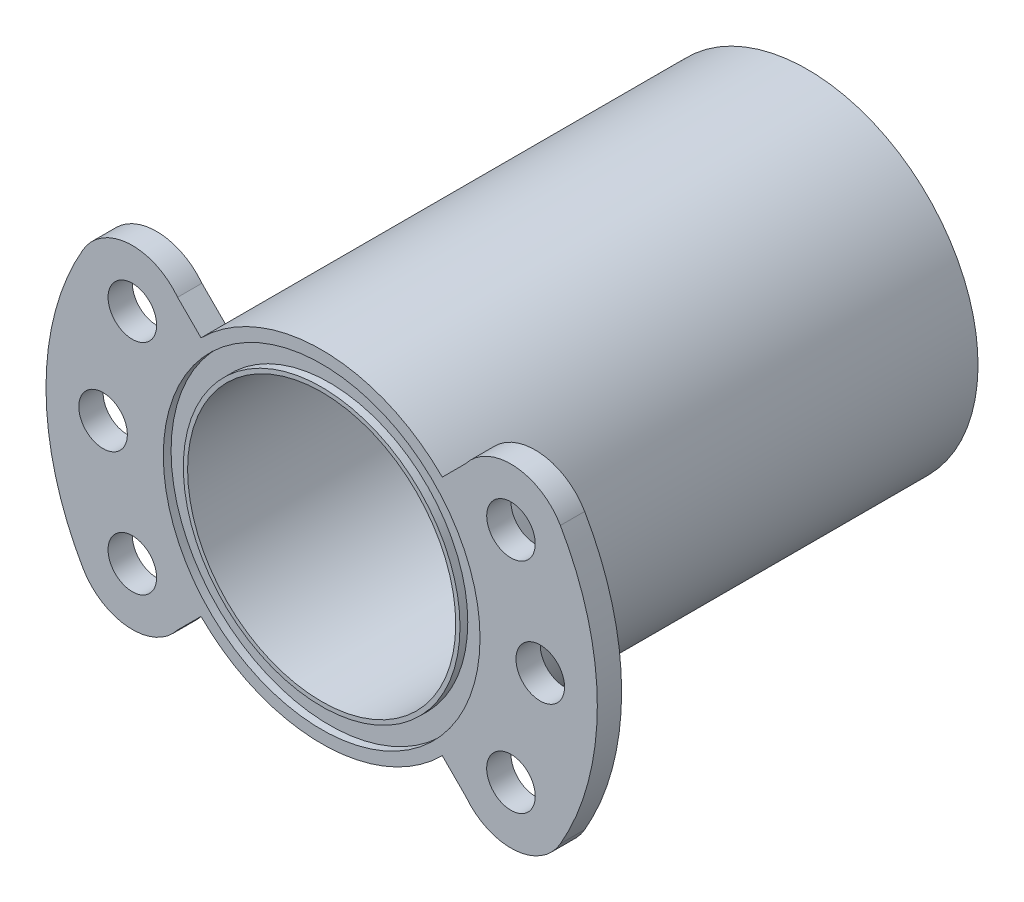
SolidWorks part; units mm, degrees
material "6061-T6 (SS)"
ref_plane "Front Plane" through (0, 0, 0) normal (0, 0, 1) x (1, 0, 0)
ref_plane "Top Plane" through (0, 0, 0) normal (0, 1, 0) x (1, 0, 0)
ref_plane "Right Plane" through (0, 0, 0) normal (1, 0, 0) x (0, 0, -1)
sketch "Sketch1" plane through (0, 0, 0) normal (0, 0, 1) x (1, 0, 0)
  circle A0 centre (0, 0) radius 17.526
  circle A1 centre (0, 0) radius 21.082
  dimension "D1" = 3.556
  dimension "D2" = 35.052
  dimension "D3" = 42.164
extrude "Boss-Extrude1" add sketch "Sketch1" along normal blind 254
sketch "Sketch2" plane through (0, 0, 0) normal (0, 0, -1) x (-1, 0, 0)
  circle A0 centre (0, 0) radius 21.082
extrude "Boss-Extrude2" add sketch "Sketch2" along normal blind 6.35
sketch "Sketch3" plane through (0, 0, 254) normal (0, 0, 1) x (1, 0, 0)
  circle A0 centre (0, 0) radius 25.8684
extrude "Cut-Extrude1" cut sketch "Sketch3" against normal blind 127
sketch "Sketch4" plane through (0, 0, 127) normal (0, 0, 1) x (1, 0, 0)
  circle A0 centre (0, 0) radius 19.0911
  circle A1 centre (0, 0) radius 34.925
  dimension "D1" = 69.85
extrude "Boss-Extrude3" add sketch "Sketch4" against normal blind 3.175
sketch "Sketch5" plane through (0, 0, 127) normal (0, 0, 1) x (1, 0, 0)
  line L0 (0, 0) -> (0, 17.526)
  line L1 (0, 17.526) -> (0, 34.925)
  circle A0 centre (0, 0) radius 17.526 construction
  circle A3 centre (0, 0) radius 34.925 construction
  circle A4 centre (0, 28.575) radius 3.175
  circle A5 centre (0, 28.575) radius 6.35
  dimension "D1" = 6.35
  dimension "D2" = 12.7
  dimension "D3" = 28.575
extrude "Cut-Extrude2" cut sketch "Sketch5" against normal through all contours L1 A4 | L1 A4
pattern_circular "CirPattern1" count 12 every 30 about axis through (0, 0, 0) along (0, 0, 1) of "Cut-Extrude2"
sketch "Sketch6" plane through (0, 0, -6.35) normal (0, 0, -1) x (-1, 0, 0)
  circle A0 centre (0, 0) radius 21.082
extrude "Cut-Extrude3" cut sketch "Sketch6" against normal blind 6.35
sketch "Sketch7" plane through (0, 0, 0) normal (0, 0, -1) x (-1, 0, 0)
  circle A0 centre (0, 0) radius 21.082
extrude "Boss-Extrude4" add sketch "Sketch7" against normal blind 6.35
sketch "Sketch8" plane through (0, 0, 127) normal (0, 0, 1) x (1, 0, 0)
  line L0 (14.2875, 24.7467) -> (8.763, 15.178)
  line L1 (8.763, 15.178) -> (-14.2875, -24.7467)
  line L2 (-14.2875, -24.7467) -> (-17.4625, -30.2459)
  line L3 (14.2875, 24.7467) -> (17.4625, 30.2459)
  line L4 (-24.7467, 14.2875) -> (24.7467, -14.2875)
  line L5 (24.7467, 14.2875) -> (-24.7467, -14.2875)
  line L6 (0, 0) -> (20.2056, 20.2056)
  line L7 (0, 0) -> (20.2056, -20.2056)
  line L8 (0, 0) -> (-14.2875, 24.7467)
  line L9 (0, 0) -> (-20.2056, 20.2056)
  line L10 (0, 0) -> (-20.2056, -20.2056)
  circle A0 centre (0, 0) radius 34.925
  circle A1 centre (0, 0) radius 17.526
  circle A2 centre (0, 0) radius 28.575
  circle A3 centre (24.7467, 14.2875) radius 7.4596
  circle A4 centre (24.7467, -14.2875) radius 7.4596
  circle A5 centre (-24.7467, -14.2875) radius 7.4596
  circle A6 centre (-24.7467, 14.2875) radius 7.4596
  circle A7 centre (0, 0) radius 36.0346
  circle A8 centre (0, 0) radius 21.082
  circle M4 centre (-14.2875, -24.7467) radius 3.175
  circle M5 centre (0, -28.575) radius 3.175
  circle M6 centre (14.2875, -24.7467) radius 3.175
  circle M10 centre (14.2875, 24.7467) radius 3.175
  circle M11 centre (-14.2875, 24.7467) radius 3.175
  circle M12 centre (0, 28.575) radius 3.175
  circle M14 centre (0, 0) radius 34.925
  dimension "D1" = 42.164
extrude "Cut-Extrude5" cut sketch "Sketch8" against normal through all contours A8 L0 A2 L8 M10 M12 M11 | A6 A2 L3 M11 M12 M10 M14 | A8 L8 A2 A6 L9 M11 | A8 L6 A3 A2 L0 M10 | A3 L3 A2 M14 M10 | A4 A2 L2 M6 M5 M4 M14 | A8 L1 A2 A4 L7 M4 M5 M6 | A8 L10 A5 A2 L1 M4 | A5 L2 A2 M14 M4 | A0
sketch "Sketch11" plane through (0, 0, 127) normal (0, 0, 1) x (1, 0, 0)
  circle A0 centre (24.7467, 14.2875) radius 7.4596
  circle A1 centre (0, 0) radius 36.0346
  circle A2 centre (24.7467, -14.2875) radius 7.4596
  circle A3 centre (-24.7467, -14.2875) radius 7.4596
  circle A4 centre (-24.7467, 14.2875) radius 7.4596
  arc M8 (27.8541, -21.069) -> (27.8541, 21.069) centre (0, 0) ccw
  arc M14 (-27.8541, 21.069) -> (-27.8541, -21.069) centre (0, 0) ccw
extrude "Boss-Extrude5" add sketch "Sketch11" against normal up to surface (3.175 mm away) contours A4 A1 A3 M14 | A4 M14 | A3 M14 | A2 M8 | A2 A1 A0 M8 | A0 M8
sketch "Sketch12" plane through (0, 0, 127) normal (0, 0, 1) x (1, 0, 0)
  circle A0 centre (0, 0) radius 21.082
  circle A1 centre (0, 0) radius 17.907
  dimension "D1" = 35.814
sketch "Sketch13" plane through (0, 0, 127) normal (0, 0, 1) x (1, 0, 0)
  circle A0 centre (0, 0) radius 18.0848
  circle A2 centre (0, 0) radius 20.701
  dimension "D1" = 36.1696
  dimension "D2" = 41.402
extrude "Cut-Extrude6" cut sketch "Sketch13" against normal blind 1.016
sketch "Sketch14" plane through (0, 0, 127) normal (0, 0, 1) x (1, 0, 0)
  circle A0 centre (0, 0) radius 22.3012
  circle A1 centre (0, 0) radius 20.701 construction
  circle A2 centre (0, 0) radius 20.701
  dimension "D1" = 1.6002
extrude "Boss-Extrude6" add sketch "Sketch14" against normal up to surface (3.175 mm away) up to face at (27.9217, -14.2875, 123.825)
sketch "Sketch15" plane through (0, 0, 123.825) normal (0, 0, -1) x (-1, 0, 0)
  circle A0 centre (0, 0) radius 39.9365
  circle M2 centre (24.7467, 14.2875) radius 3.175
  circle M3 centre (28.575, 0) radius 3.175
  circle M4 centre (24.7467, -14.2875) radius 3.175
  line M5 (18.8286, 18.8286) -> (15.7693, 15.7693)
  arc M6 (15.7693, 15.7693) -> (-15.7693, 15.7693) centre (0, 0) ccw
  line M7 (-15.7693, 15.7693) -> (-18.8286, 18.8286)
  arc M8 (-18.8286, 18.8286) -> (-31.2069, 18.0173) centre (-24.7467, 14.2875) ccw
  arc M9 (-31.2069, 18.0173) -> (-31.2069, -18.0173) centre (0, 0) ccw
  arc M10 (-31.2069, -18.0173) -> (-18.8286, -18.8286) centre (-24.7467, -14.2875) ccw
  line M11 (-18.8286, -18.8286) -> (-15.7693, -15.7693)
  arc M12 (-15.7693, -15.7693) -> (15.7693, -15.7693) centre (0, 0) ccw
  line M13 (15.7693, -15.7693) -> (18.8286, -18.8286)
  arc M14 (18.8286, -18.8286) -> (31.2069, -18.0173) centre (24.7467, -14.2875) ccw
  arc M15 (31.2069, -18.0173) -> (31.2069, 18.0173) centre (0, 0) ccw
  arc M16 (31.2069, 18.0173) -> (18.8286, 18.8286) centre (24.7467, 14.2875) ccw
  circle M17 centre (0, 0) radius 21.082
  circle M18 centre (-24.7467, -14.2875) radius 3.175
  circle M19 centre (-28.575, 0) radius 3.175
  circle M20 centre (-24.7467, 14.2875) radius 3.175
extrude "Boss-Extrude7" add sketch "Sketch15" along normal up to surface (123.825 mm away) contours M16 M5 M6 M7 M8 M9 M10 M11 M12 M13 M14 M15 M3 M18 M20 M19 M17 M4 M2
sketch "Sketch16" plane through (0, 0, 0) normal (0.7071, 0.7071, 0) x (0.7071, -0.7071, 0)
  line L0 (-24.4644, -127) -> (-24.4644, -123.825)
  line L1 (-22.3012, -127) -> (-26.6277, -127) construction
  dimension "D1" = 3.175
ref_plane "Plane1" through (0, 0, 123.825) normal (0, 0, 1) x (1, 0, 0)
sketch "Sketch17" plane through (0, 0, 123.825) normal (0, 0, 1) x (1, 0, 0)
  circle A0 centre (0, 0) radius 47.4648
  circle A1 centre (0, 0) radius 22.3012
  arc A2 (15.7693, 15.7693) -> (-15.7693, 15.7693) centre (0, 0) ccw construction
  dimension "D1" = 0
extrude "Cut-Extrude7" cut sketch "Sketch17" against normal offset from surface (120.65 mm away) 3.175
sketch "Sketch18" plane through (0, 0, 127) normal (0, 0, 1) x (1, 0, 0)
  circle A0 centre (0, 0) radius 17.526
extrude "Cut-Extrude8" cut sketch "Sketch18" against normal through all
sketch "Sketch19" plane through (0, 0, 0) normal (0, 0, -1) x (-1, 0, 0)
  circle A0 centre (0, 0) radius 18.0848
  circle A1 centre (0, 0) radius 20.701
  dimension "D1" = 41.402
  dimension "D2" = 36.1696
extrude "Cut-Extrude9" cut sketch "Sketch19" against normal blind 1.016
sketch "Sketch20" plane through (0, 0, 0) normal (0, 0, -1) x (-1, 0, 0)
  circle A0 centre (0, 0) radius 43.3554
extrude "Cut-Extrude10" cut sketch "Sketch20" against normal blind 25.4
sketch "Sketch21" plane through (0, 0, 25.4) normal (0, 0, -1) x (-1, 0, 0)
  circle A0 centre (0, 0) radius 25.9277
extrude "Cut-Extrude11" cut sketch "Sketch21" against normal blind 38.1
sketch "Sketch22" plane through (0, 0, 63.5) normal (0, 0, -1) x (-1, 0, 0)
  circle A0 centre (0, 0) radius 20.063
extrude "Boss-Extrude8" add sketch "Sketch22" against normal blind 3.175
